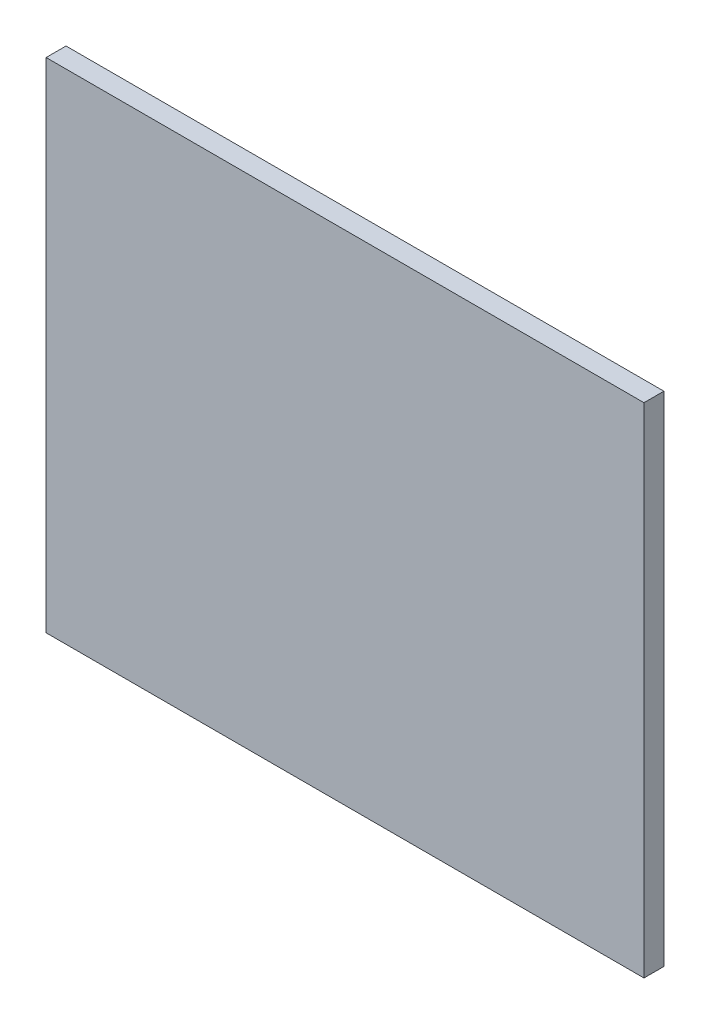
SolidWorks part; units mm, degrees
ref_plane "Alzado" through (0, 0, 0) normal (0, 0, 1) x (1, 0, 0)
ref_plane "Planta" through (0, 0, 0) normal (0, 1, 0) x (1, 0, 0)
ref_plane "Vista lateral" through (0, 0, 0) normal (1, 0, 0) x (0, 0, -1)
sketch "Croquis1" plane through (0, 0, 0) normal (0, 0, 1) x (1, 0, 0)
  line L1 (30, -25) -> (-30, -25)
  line L2 (30, -25) -> (30, 25)
  line L3 (30, 25) -> (-30, 25)
  line L4 (-30, -25) -> (-30, 25)
  line L5 (30, -25) -> (-30, 25) construction
  line L6 (30, 25) -> (-30, -25) construction
  point P0 (0, 0)
  dimension "D1" = 50
  dimension "D2" = 60
extrude "Saliente-Extruir1" add sketch "Croquis1" along normal blind 2
